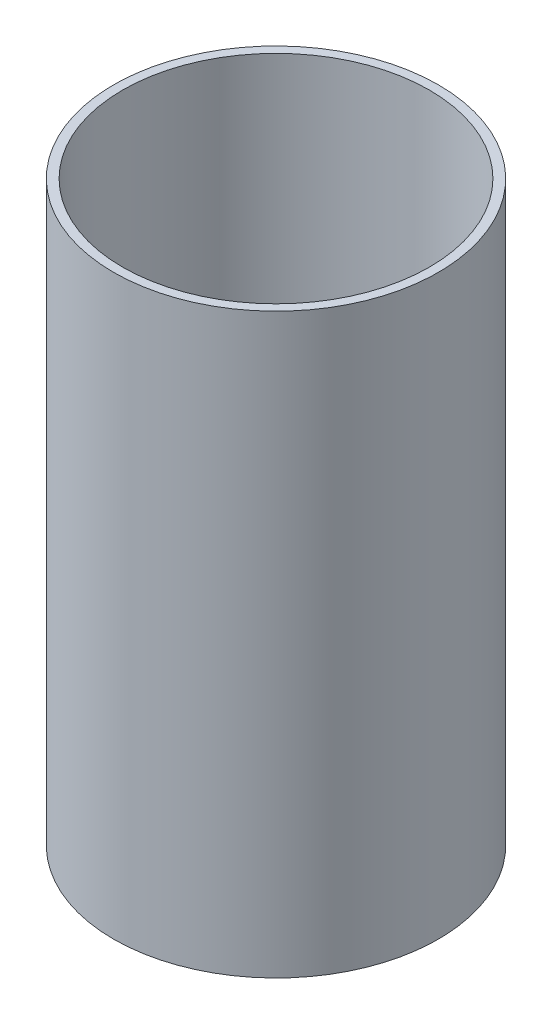
SolidWorks part; units mm, degrees
ref_plane "Front Plane" through (0, 0, 0) normal (0, 0, 1) x (1, 0, 0)
ref_plane "Top Plane" through (0, 0, 0) normal (0, 1, 0) x (1, 0, 0)
ref_plane "Right Plane" through (0, 0, 0) normal (1, 0, 0) x (0, 0, -1)
sketch "Sketch1" plane through (0, 0, 0) normal (0, 1, 0) x (1, 0, 0)
  circle A0 centre (0, 0) radius 26.9875
  circle A1 centre (0, 0) radius 28.575
  dimension "D1" = 57.15
  dimension "D2" = 53.975
extrude "Boss-Extrude1" add sketch "Sketch1" along normal blind 101.6
